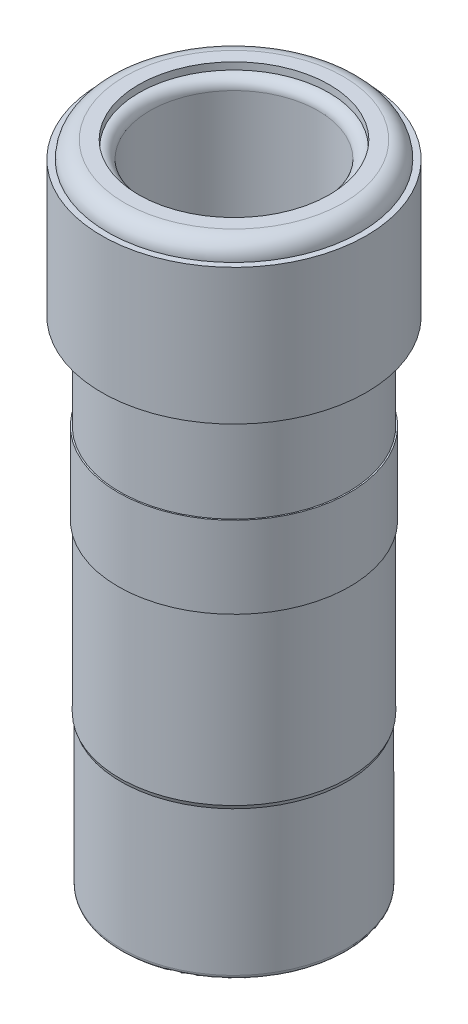
SolidWorks part; units mm, degrees
ref_plane "Front" through (0, 0, 0) normal (0, 0, 1) x (1, 0, 0)
ref_plane "Top" through (0, 0, 0) normal (0, 1, 0) x (1, 0, 0)
ref_plane "Right" through (0, 0, 0) normal (1, 0, 0) x (0, 0, -1)
sketch "Esboço1" plane through (0, 0, 0) normal (0, 0, 1) x (1, 0, 0)
  line L0 (0, 0) -> (0, 23.1) construction
  line L6 (-3.37, 10.5013) -> (-3.41, 10.5013)
  line L7 (-3.9, 18.6) -> (-3.37, 18.6)
  line L8 (-3.37, 18.6) -> (-3.37, 15.8)
  line L9 (-3.37, 4.1013) -> (-2.725, 2.3292)
  line L10 (-2.725, 2.3292) -> (-2.725, 0)
  line L15 (-3.37, 15.8) -> (-3.43, 15.8)
  line L16 (-3.37, 13.4) -> (-3.43, 13.4)
  line L17 (-3.41, 10.5013) -> (-3.41, 8.1013)
  line L18 (-3.41, 8.1013) -> (-3.37, 8.1013)
  line L19 (-3.37, 13.4) -> (-3.37, 10.5013)
  line L20 (-3.37, 8.1013) -> (-3.37, 4.1013)
  line L21 (-3.43, 13.4) -> (-3.43, 15.8)
  line L22 (-3.9, 22.6) -> (-3.9, 18.6)
  line L23 (-2.725, 0) -> (0, 0)
  line L24 (-3.9, 22.6) -> (-3.725, 22.6)
  line L25 (0, 23.1) -> (0, 0) construction
  line L27 (-3.225, 23.1) -> (0, 23.1)
  line L29 (0, 23.1) -> (0, 0)
  arc A1 (-3.225, 23.1) -> (-3.725, 22.6) centre (-3.225, 22.6) ccw
  point P5 (-3.725, 23.1)
  point P20 (-3.37, 17.2)
  dimension "D9" = 0.5
  dimension "D8" = 1
  dimension "D3" = 22.6
  dimension "D4" = 4
  dimension "D5" = 5.45
  dimension "D6" = 20.2708
  dimension "D7" = 0.5
  dimension "D10" = 0.5
  dimension "D11" = 2.8
  dimension "D12" = 2.4
  dimension "D13" = 20
  dimension "D14" = 3.725
  dimension "D16" = 7.8
  dimension "D17" = 0.06
  dimension "D18" = 6.74
  dimension "D19" = 2.4
  dimension "D20" = 4
  dimension "D21" = 6.74
  dimension "D22" = 0.04
  dimension "D23" = 6.82
  dimension "D24" = 6.86
revolve "Revolução1" add sketch "Esboço1" angle 360 about L0
sketch "Esboço3" plane through (0, 0, 0) normal (0, -1, 0) x (1, 0, 0)
  circle A0 centre (0, 0) radius 1.5
  dimension "D1" = 3
extrude "Corte-extrusão1" cut sketch "Esboço3" against normal blind 1.8
sketch "Esboço5" plane through (0, 0, 0) normal (1, 0, 0) x (0, 0, -1)
  line L0 (0, 0) -> (0, 22.6) construction
  line L1 (-1.5, 0) -> (1.5, 0) construction
  line L2 (3.9, 22.6) -> (-3.9, 22.6) construction
  line L3 (-0.5892, 0) -> (0.5892, 0)
  line L4 (0.5892, 0) -> (0.4, 1.8)
  line L5 (0.4, 1.8) -> (-0.4, 1.8)
  line L6 (-0.5892, 0) -> (-0.4, 1.8)
  point P10 (0, 1.8)
  dimension "D1" = 0.8
  dimension "D2" = 1.8
  dimension "D3" = 6
extrude "Corte-extrusão2" cut sketch "Esboço5" against normal through all both and the other way through all
sketch "Esboço6" plane through (0, 0, 0) normal (0, 0, 1) x (1, 0, 0)
  line L0 (3.9, 22.6) -> (-3.9, 22.6) construction
  line L1 (2.8105, 23.1) -> (0, 23.1)
  line L2 (0, 22.6) -> (0, 0) construction
  line L3 (0, 23.1) -> (0, 22.6)
  line L4 (2.46, 10.9) -> (2.26, 10.9)
  line L5 (2.48, 22.6) -> (2.48, 17.9)
  line L6 (2.45, 9.1035) -> (1.75, 6.4911)
  line L7 (1.75, 6.4911) -> (1.75, 3.4)
  line L8 (1.75, 3.4) -> (1.5, 3.4)
  line L9 (2.8, 22.8993) -> (2.8105, 23.1)
  line L10 (0, 22.6) -> (0, 23.1) construction
  line L11 (3.225, 23.1) -> (-3.225, 23.1) construction
  line L12 (0, 22.6) -> (0, 3.9)
  line L14 (2.26, 10.9) -> (2.45, 9.8225)
  line L15 (2.465, 13.2) -> (2.265, 13.2)
  line L16 (2.265, 13.2) -> (2.46, 12.0941)
  line L17 (2.48, 17.9) -> (2.28, 17.9)
  line L18 (2.28, 17.9) -> (2.48, 16.7657)
  line L19 (2.45, 9.8225) -> (2.45, 9.1035)
  line L20 (2.46, 12.0941) -> (2.46, 10.9)
  line L21 (2.48, 16.7657) -> (2.465, 13.2)
  line L22 (-2.6605, 0) -> (2.6605, 0) construction
  line L23 (0, 0) -> (0, 3.4) construction
  arc A0 (2.48, 22.6) -> (2.8, 22.8993) centre (2.78, 22.6) cw
  arc A1 (1.5, 3.4) -> (0, 3.9) centre (0, 1.4) ccw
  dimension "D7" = 0.2
  dimension "D16" = 15
  dimension "D10" = 0.2
  dimension "D19" = 0.3
  dimension "D14" = 2.5
  dimension "D3" = 9.4
  dimension "D4" = 10
  dimension "D5" = 0.2
  dimension "D6" = 11.7
  dimension "D8" = 10
  dimension "D9" = 15
  dimension "D11" = 10
  dimension "D12" = 3.0911
  dimension "D13" = 0.5
  dimension "D15" = 19.7
  dimension "D17" = 3.5
  dimension "D18" = 3
  dimension "D20" = 5.6
  dimension "D21" = 3
  dimension "D22" = 4.7
  dimension "D23" = 2.48
  dimension "D24" = 2.46
  dimension "D25" = 2.46
  dimension "D26" = 4.93
  dimension "D27" = 4.9
  dimension "D28" = 4.9
revolve "Corte-Revolução1" cut sketch "Esboço6" angle 360 about L2
fillet "Filete1" radius 0.2 1 edges at (-1.75, 3.4, 0)
sketch "Esboço9" plane through (0, 0, 0) normal (0, 0, 1) x (1, 0, 0)
  line L0 (0, 0) -> (0, 43.223) construction
  line L5 (-6.0049, 22.6) -> (-3.9, 22.6)
  line L6 (-3.37, 8.4914) -> (-3.33, 8.3815)
  line L7 (-3.9, 18.6) -> (-3.37, 18.6)
  line L8 (-3.37, 18.6) -> (-3.37, 15.8)
  line L9 (-3.33, 3.9914) -> (-2.725, 2.3292)
  line L15 (-3.37, 15.8) -> (-3.41, 15.8)
  line L16 (-3.37, 13.4) -> (-3.41, 13.4)
  line L17 (-3.33, 8.3815) -> (-3.33, 3.9914)
  line L18 (-2.6605, 0) -> (2.6605, 0) construction
  line L19 (-2.725, 2.3292) -> (-2.725, 1.8) construction
  line L20 (-3.37, 13.4) -> (-3.37, 8.4914)
  line L21 (-3.41, 13.4) -> (-3.41, 15.8)
  line L22 (-3.37, 4.1013) -> (-2.725, 2.3292) construction
  line L23 (-3.9, 22.6) -> (-3.9, 18.6)
  line L26 (-3.9, 18.6) -> (3.9, 18.6) construction
  line L27 (-6.0049, 22.6) -> (-6.0049, 2.3292)
  line L28 (-6.0049, 2.3292) -> (-2.725, 2.3292)
  point P21 (-3.37, 17.2)
  dimension "D3" = 6.74
  dimension "D4" = 6.66
  dimension "D5" = 4.5
  dimension "D8" = 4
  dimension "D9" = 7.8
  dimension "D17" = 20
  dimension "D18" = 20
  dimension "D19" = 2.4
  dimension "2,65" = 2.8
  dimension "0,05" = 0.04
revolve "Corte-Revolução2" cut sketch "Esboço9" angle 360 about L0
scale "Escala1" [suppressed]
sketch "Esboço12" plane through (0, 0, 0) normal (0, -1, 0) x (1, 0, 0)
  circle A0 centre (0, 0) radius 4.6698
extrude "Corte-extrusão3" cut sketch "Esboço12" against normal blind 4
ref_plane "Plano1" through (0, 4.5, 0) normal (0, -1, 0) x (-1, 0, 0)
sketch "Esboço15" plane through (0, 4.5, 0) normal (0, -1, 0) x (-1, 0, 0)
  circle A1 centre (0, 0) radius 2.3534
extrude "Ressalto-extrusão2" add sketch "Esboço15" against normal blind 1
fillet "Filete2" radius 0.13 4 edges at (3.33, 4, 0) (1.75, 4, 0) (-1.75, 6.4911, 0) (-2.45, 9.1035, 0)
sketch "Esboço16" plane through (0, 4.5, 0) normal (0, -1, 0) x (1, 0, 0)
  circle A4 centre (0, 0) radius 2.48
extrude "Corte-extrusão4" cut sketch "Esboço16" against normal through all both and the other way through all
ref_plane "Plano2" through (0, 8, 0) normal (0, -1, 0) x (-1, 0, 0)
sketch "Esboço18" plane through (0, 8, 0) normal (0, -1, 0) x (-1, 0, 0)
  circle A0 centre (0, 0) radius 2.48
extrude "Ressalto-extrusão3" add sketch "Esboço18" against normal blind 1.5
sketch "Esboço19" plane through (0, 8, 0) normal (0, -1, 0) x (1, 0, 0)
  circle A0 centre (0, 0) radius 0.75
extrude "Ressalto-extrusão4" add sketch "Esboço19" along normal up to surface (4 mm away) up to face at (2.48, 4, 0)
fillet "Filete3" radius 0.5 1 edges at (0.75, 4, 0)
sketch "Esboço20" plane through (0, 9.5, 0) normal (0, 1, 0) x (1, 0, 0)
  circle A1 centre (0, 0) radius 1.7992
extrude "Corte-extrusão5" cut sketch "Esboço20" against normal blind 10
